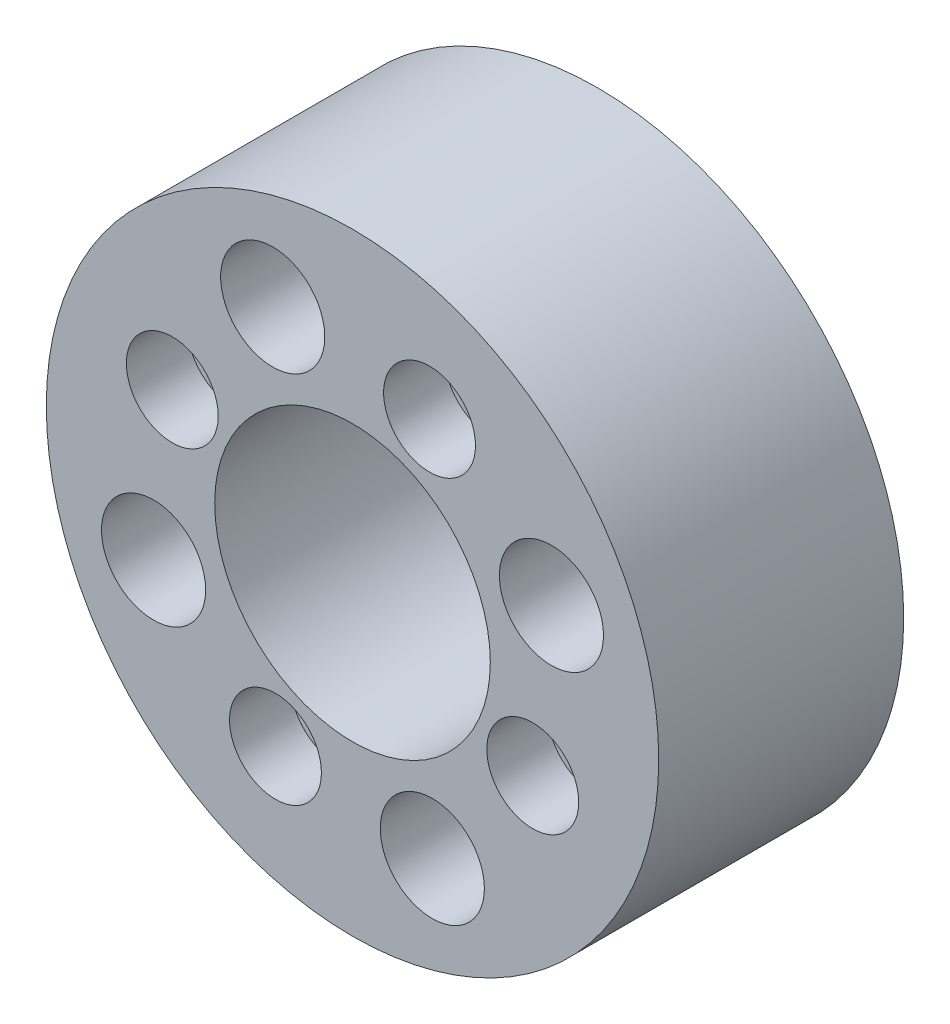
SolidWorks part; units mm, degrees
ref_plane "Plan de face" through (0, 0, 0) normal (0, 0, 1) x (1, 0, 0)
ref_plane "Plan de dessus" through (0, 0, 0) normal (0, 1, 0) x (1, 0, 0)
ref_plane "Plan de droite" through (0, 0, 0) normal (1, 0, 0) x (0, 0, -1)
sketch "Esquisse1" plane through (0, 0, 0) normal (0, 0, 1) x (1, 0, 0)
  circle A0 centre (0, 0) radius 11.25
  circle A1 centre (0, 0) radius 25
  dimension "D1" = 22.5
  dimension "D2" = 50
extrude "Boss.-Extru.1" add sketch "Esquisse1" along normal blind 20
sketch "Esquisse2" plane through (0, 0, 20) normal (0, 0, 1) x (1, 0, 0)
  line L0 (-14.7134, 6.2862) -> (-5.9572, 14.8496) construction
  line L1 (-5.9572, 14.8496) -> (6.2896, 14.712) construction
  line L2 (-6.2896, -14.712) -> (5.9572, -14.8496) construction
  line L3 (5.9572, -14.8496) -> (14.7134, -6.2862) construction
  line L4 (-5.9572, 14.8496) -> (0, 0) construction
  line L5 (0, 0) -> (5.9572, -14.8496) construction
  circle A0 centre (0, 0) radius 16 construction
  circle A2 centre (-14.7134, 6.2862) radius 2.5
  circle A3 centre (6.2896, 14.712) radius 2.5
  circle A4 centre (14.7134, -6.2862) radius 2.5
  circle A6 centre (-6.2896, -14.712) radius 2.5
  dimension "D1" = 32
  dimension "D3" = 5
  dimension "D2" = 22.63
extrude "Enlèv. mat.-Extru.1" cut sketch "Esquisse2" against normal through all
sketch "Esquisse4" plane through (0, 0, 20) normal (0, 0, 1) x (1, 0, 0)
  circle A0 centre (-6.2896, -14.712) radius 3.75
  circle A2 centre (14.7134, -6.2862) radius 3.75
  circle A3 centre (6.2896, 14.712) radius 3.75
  circle A5 centre (-14.7134, 6.2862) radius 3.75
  dimension "D1" = 7.5
extrude "Enlèv. mat.-Extru.2" cut sketch "Esquisse4" against normal blind 5
sketch "Esquisse5" plane through (0, 0, 20) normal (0, 0, 1) x (1, 0, 0)
  line L0 (23.2025, 9.3082) -> (0, 0) construction
  line L1 (23.2025, 9.3082) -> (14.7134, -6.2862) construction
  line L2 (14.7134, -6.2862) -> (6.2896, 14.712) construction
  line L3 (6.2896, 14.712) -> (23.2025, 9.3082) construction
  circle A2 centre (0, 0) radius 25 construction
ref_plane "Plan1" through (0, 0, 20) normal (-0.9281, -0.3723, 0) x (0, 0, 1)
ref_plane "Plan2" through (0, 0, 0) normal (-0.3723, 0.9281, 0) x (-0.9281, -0.3723, 0)
sketch "Esquisse12" plane through (0, 0, 20) normal (0, 0, 1) x (1, 0, 0)
  line L0 (16.2418, 6.5157) -> (6.5157, -16.2418) construction
  line L1 (6.5157, -16.2418) -> (-16.2418, -6.5157) construction
  line L2 (-16.2418, -6.5157) -> (-6.5157, 16.2418) construction
  line L3 (-6.5157, 16.2418) -> (16.2418, 6.5157) construction
  line L5 (16.2418, 6.5157) -> (-16.2418, -6.5157) construction
  line L6 (4.1065, -20.9794) -> (8.925, -11.5041) construction
  circle A0 centre (16.2418, 6.5157) radius 4.25
  circle A1 centre (-16.2418, -6.5157) radius 4.25
  circle A2 centre (6.5157, -16.2418) radius 4.25
  circle A3 centre (-6.5157, 16.2418) radius 4.25
  point P2 (0, 0)
  dimension "D1" = 8.5
extrude "Enlèv. mat.-Extru.6" cut sketch "Esquisse12" against normal blind 7.5
sketch "Esquisse16" plane through (0, 0, 0) normal (-0.3723, 0.9281, 0) x (-0.9281, -0.3723, 0)
  line L0 (2.6286, 19.5726) -> (-2.6286, 19.5726) construction
  line L2 (0, 6.25) -> (0, 33.75) construction
  point P4 (0, 19.5726)
equation "\"D3@Esquisse13\"=\"D1@Esquisse13\""
